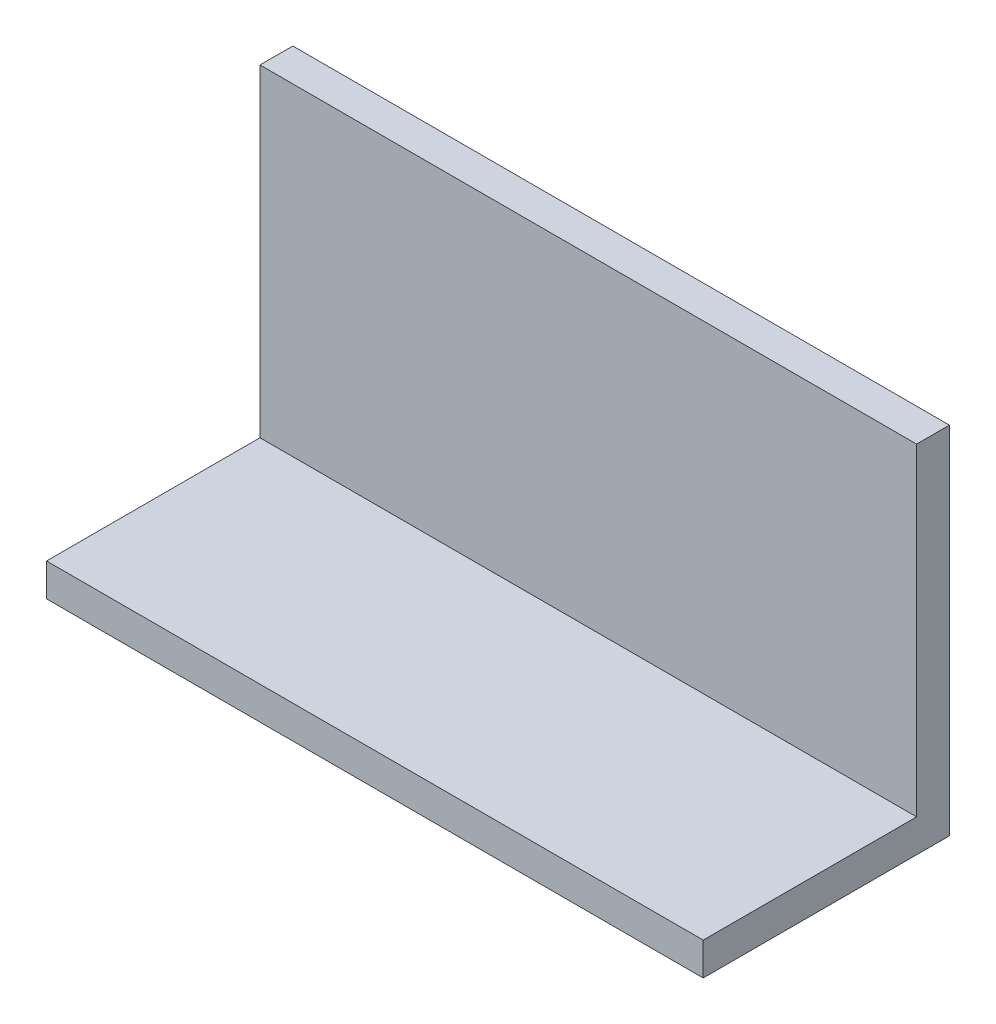
SolidWorks part; units mm, degrees
ref_plane "前视基准面" through (0, 0, 0) normal (0, 0, 1) x (1, 0, 0)
ref_plane "上视基准面" through (0, 0, 0) normal (0, 1, 0) x (1, 0, 0)
ref_plane "右视基准面" through (0, 0, 0) normal (1, 0, 0) x (0, 0, -1)
sketch "草图1" plane through (0, 0, 0) normal (0, 0, 1) x (1, 0, 0)
  line L1 (0, 0) -> (240, 0)
  line L2 (0, 0) -> (0, 130)
  line L3 (0, 130) -> (240, 130)
  line L4 (240, 0) -> (240, 130)
  dimension "D1" = 240
  dimension "D2" = 130
extrude "凸台-拉伸1" add sketch "草图1" along normal blind 90
sketch "草图2" plane through (0, 0, 0) normal (-1, 0, 0) x (0, 0, 1)
  line L0 (0, 130) -> (0, 0) construction
  line L1 (90, 130) -> (12, 130)
  line L2 (90, 130) -> (90, 12)
  line L3 (90, 12) -> (12, 12)
  line L4 (12, 130) -> (12, 12)
  line L5 (90, 0) -> (0, 0) construction
  dimension "D1" = 12
  dimension "D2" = 12
extrude "切除-拉伸1" cut sketch "草图2" against normal through all
